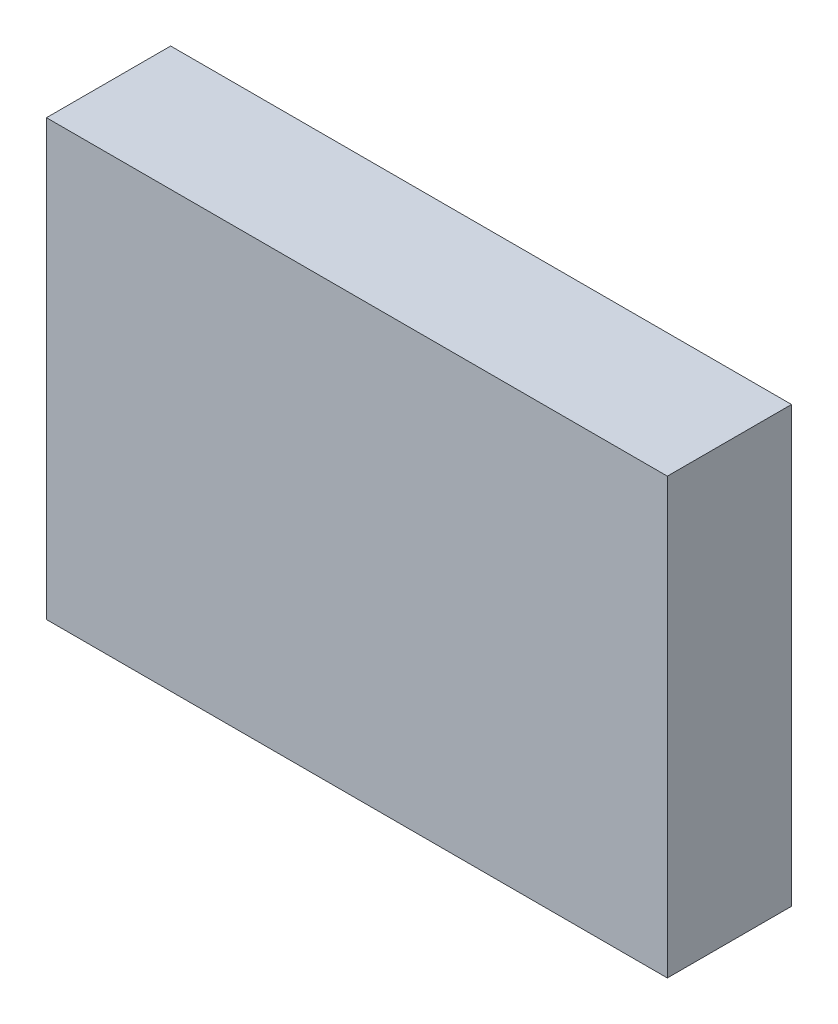
SolidWorks part; units mm, degrees
ref_plane "前视基准面" through (0, 0, 0) normal (0, 0, 1) x (1, 0, 0)
ref_plane "上视基准面" through (0, 0, 0) normal (0, 1, 0) x (1, 0, 0)
ref_plane "右视基准面" through (0, 0, 0) normal (1, 0, 0) x (0, 0, -1)
other "Configuration Table"
sketch "草图1" plane through (0, 0, 0) normal (0, 0, 1) x (1, 0, 0)
  line L1 (-50, -35) -> (50, -35)
  line L2 (-50, -35) -> (-50, 35)
  line L3 (-50, 35) -> (50, 35)
  line L4 (50, -35) -> (50, 35)
  line L5 (-50, -35) -> (50, 35) construction
  line L6 (-50, 35) -> (50, -35) construction
  point P0 (0, 0)
extrude "凸台-拉伸1" add sketch "草图1" along normal blind 20
